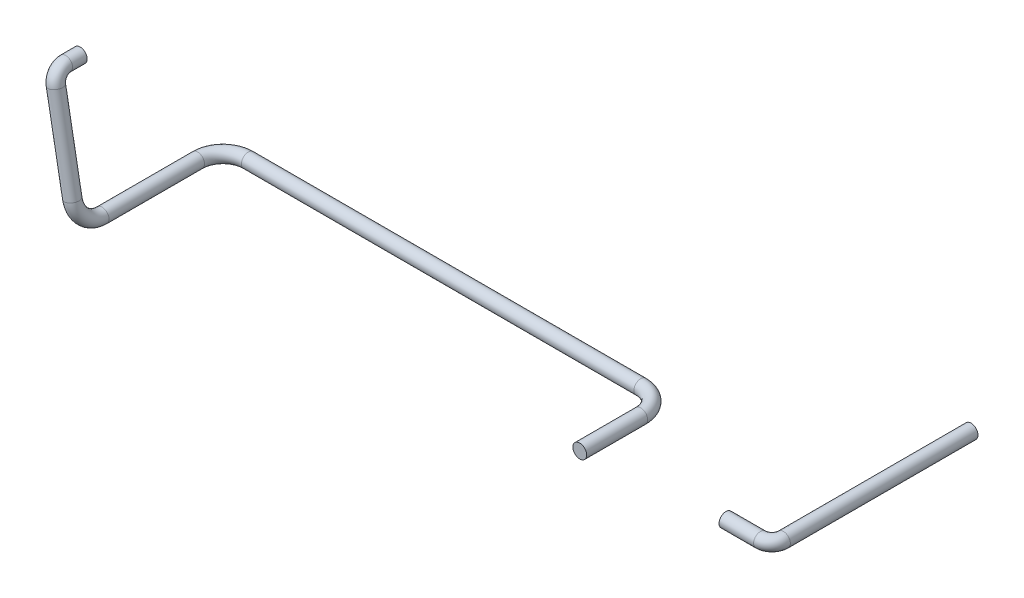
SolidWorks part; units mm, degrees
material "PVC 0.007 Plasticized"
ref_plane "Front Plane" through (0, 0, 0) normal (0, 0, 1) x (1, 0, 0)
ref_plane "Top Plane" through (0, 0, 0) normal (0, 1, 0) x (1, 0, 0)
ref_plane "Right Plane" through (0, 0, 0) normal (1, 0, 0) x (0, 0, -1)
sketch3d "Pipe path 1"
  line L0 (285, 0, 344) -> (285, 0, 356.65)
  line L1 (286.8515, -10.1831, 367) -> (301.0645, -88.3549, 367)
  line L2 (305, -110, 345) -> (305, -110, 262)
  line L3 (327, -110, 240) -> (668, -110, 240)
  line L4 (690, -110, 262) -> (690, -110, 315)
  arc A0 (285, 0, 356.65) -> (286.8515, -10.1831, 367) centre (286.8515, -10.1831, 356.65) ccw
  arc A1 (301.0645, -88.3549, 367) -> (305, -110, 345) centre (301.0645, -88.3549, 345) ccw
  arc A2 (305, -110, 262) -> (327, -110, 240) centre (327, -110, 262) ccw
  arc A3 (668, -110, 240) -> (690, -110, 262) centre (668, -110, 262) ccw
  point P8 (285, 0, 367)
  point P9 (297.0345, -8.3316, 356.65)
  point P12 (305, -110, 367)
  point P13 (322.7097, -84.4194, 345)
  point P16 (305, -110, 240)
  point P17 (327, -132, 262)
  point P20 (690, -110, 240)
  point P21 (668, -132, 262)
  dimension "D1" = 10.35
  dimension "D2" = 22
  dimension "D3" = 22
  dimension "D4" = 22
sweep "Pipe 1" add path "Pipe path 1" circular profile diameter 12 parameters "D3"=12
sketch3d "Pipe path 2"
  line L0 (855, -60, 353) -> (885, -60, 353)
  line L1 (895, -60, 343) -> (895, -60, 180)
  arc A0 (885, -60, 353) -> (895, -60, 343) centre (885, -60, 343) ccw
  point P5 (895, -60, 353)
  point P6 (885, -50, 343)
  dimension "D1" = 10
sweep "Pipe 2" add path "Pipe path 2" circular profile diameter 12 parameters "D3"=12
